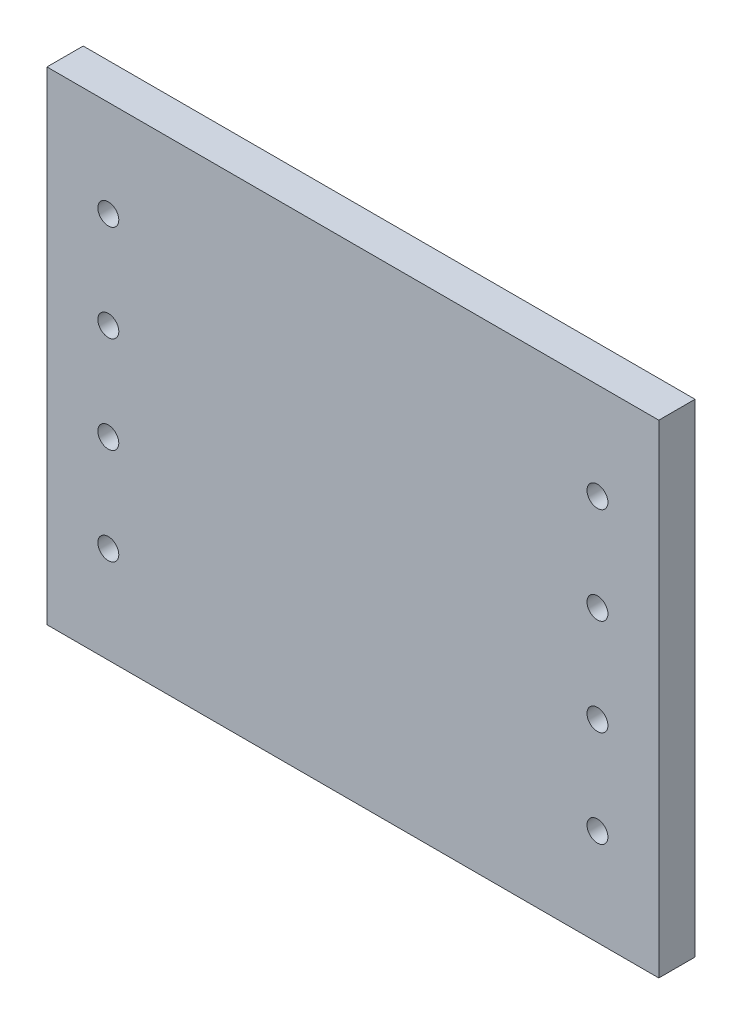
SolidWorks part; units mm, degrees
ref_plane "Front" through (0, 0, 0) normal (0, 0, 1) x (1, 0, 0)
ref_plane "Top" through (0, 0, 0) normal (0, 1, 0) x (1, 0, 0)
ref_plane "Right" through (0, 0, 0) normal (1, 0, 0) x (0, 0, -1)
other "Configuration Table"
sketch "Sketch1" plane through (0, 0, 0) normal (0, 0, 1) x (1, 0, 0)
  line L1 (23.481, 212.5625) -> (345.172, 212.5625)
  line L2 (345.172, 441.1625) -> (345.172, 237.9625) construction
  line L3 (23.481, 466.5625) -> (345.172, 466.5625)
  line L4 (345.172, 212.5625) -> (345.172, 466.5625)
  line L5 (345.172, 441.1625) -> (345.172, 237.9625) construction
  line L6 (23.481, 466.5625) -> (23.481, 212.5625)
  dimension "D2" = 254
extrude "Base-Extrude" add sketch "Sketch1" along normal blind 19.05
sketch "Sketch2" plane through (0, 0, 0) normal (0, 0, -1) x (-1, 0, 0)
  line L1 (-345.172, 466.5625) -> (-23.481, 466.5625) construction
  line L2 (-345.172, 466.5625) -> (-23.481, 466.5625) construction
  line L3 (-273.2265, 392.2739) -> (-273.2265, 245.7761)
  line L4 (-23.481, 212.5625) -> (-345.172, 212.5625) construction
  line L5 (-105.1421, 403.0625) -> (-263.511, 403.0625)
  line L6 (-105.1421, 403.0625) -> (-95.4265, 392.2739)
  line L7 (-263.511, 403.0625) -> (-273.2265, 392.2739)
  line L8 (-273.2265, 245.7761) -> (-95.4265, 245.7761)
  line L9 (-95.4265, 392.2739) -> (-95.4265, 245.7761)
  line L10 (-23.481, 212.5625) -> (-345.172, 212.5625) construction
  line L11 (-184.3265, 466.5625) -> (-184.3265, 212.5625) construction
  dimension "D1" = 177.8
extrude "Boss-Extrude1" add sketch "Sketch2" along normal blind 15.875
sketch "Sketch3" plane through (0, 0, -15.875) normal (0, 0, -1) x (-1, 0, 0)
  line L24 (-254.1765, 264.8261) -> (-114.4765, 264.8261)
  line L25 (-114.4765, 264.8261) -> (-114.4765, 384.0125)
  line L26 (-114.4765, 384.0125) -> (-254.1765, 384.0125)
  line L27 (-254.1765, 384.0125) -> (-254.1765, 264.8261)
  line L28 (-254.1765, 264.8261) -> (-114.4765, 264.8261)
  line L29 (-114.4765, 264.8261) -> (-114.4765, 384.0125)
  line L30 (-114.4765, 384.0125) -> (-254.1765, 384.0125)
  line L31 (-254.1765, 384.0125) -> (-254.1765, 264.8261)
  dimension "D2" = 19.05
extrude "Cut-Extrude1" cut sketch "Sketch3" against normal up to surface (15.875 mm away) up to face at (184.3265, 339.5625, 0)
fillet "Fillet3" radius 2.54 6 edges at (95.4265, 319.025, 0) (100.2843, 397.6682, 0) (184.3265, 403.0625, 0) (268.3688, 397.6682, 0) (273.2265, 319.025, 0) (184.3265, 245.7761, 0)
fillet "Fillet5" radius 6.35 4 edges at (254.1765, 264.8261, -7.9375) (114.4765, 264.8261, -7.9375) (114.4765, 384.0125, -7.9375) (254.1765, 384.0125, -7.9375)
fillet "Fillet6" radius 2.54 8 edges at (254.1765, 324.4193, 0) (184.3265, 384.0125, 0) (184.3265, 264.8261, 0) (114.4765, 324.4193, 0) (116.3364, 266.686, 0) (116.3364, 382.1526, 0) (252.3167, 266.686, 0) (252.3167, 382.1526, 0)
hole_wizard "CBORE for M10 SHCS1" positions "Sketch7" profile "Sketch6" counterbore size "M10" standard "Ansi Metric" end condition through all
sketch "Sketch7" plane through (0, 0, 0) normal (0, 0, -1) x (-1, 0, 0)
  line L0 (-345.172, 212.5625) -> (-345.172, 466.5625) construction
  line L1 (-345.172, 466.5625) -> (-23.481, 466.5625) construction
  point P0 (-312.914, 415.7625)
  dimension "D1" = 32.258
  dimension "D2" = 50.8
sketch "Sketch6" plane through (312.914, 415.7625, 0) normal (1, 0, 0) x (0, 1, 0)
  line L0 (0, 0) -> (0, 19.05)
  line L1 (0, 19.05) -> (5.5, 19.05)
  line L3 (5.5, 19.05) -> (5.5, 10)
  line L4 (5.5, 10) -> (9, 10)
  line L5 (9, 10) -> (9, 0)
  line L7 (9, 0) -> (0, 0)
  line L11 (0, -6.35) -> (0, 107.95) construction
  dimension "Thru Hole Dia." = 11
  dimension "Thru Hole Depth" = 19.05
  dimension "C'Bore Dia." = 18
  dimension "C'Bore Depth" = 10
pattern_linear "LPattern1" count 4 spacing 50.8 along (0, -1, 0) of "CBORE for M10 SHCS1"
hole_wizard "CBORE for M10 SHCS2" positions "Sketch9" profile "Sketch8" counterbore size "M10" standard "Ansi Metric" end condition through all
sketch "Sketch9" plane through (0, 0, 0) normal (0, 0, -1) x (-1, 0, 0)
  line L0 (-23.481, 466.5625) -> (-23.481, 212.5625) construction
  line L1 (-345.172, 466.5625) -> (-23.481, 466.5625) construction
  point P0 (-55.739, 415.7625)
  dimension "D1" = 32.258
  dimension "D2" = 50.8
sketch "Sketch8" plane through (55.739, 415.7625, 0) normal (1, 0, 0) x (0, 1, 0)
  line L0 (0, 0) -> (0, 19.05)
  line L1 (0, 19.05) -> (5.5, 19.05)
  line L3 (5.5, 19.05) -> (5.5, 10)
  line L4 (5.5, 10) -> (9, 10)
  line L5 (9, 10) -> (9, 0)
  line L7 (9, 0) -> (0, 0)
  line L11 (0, -6.35) -> (0, 107.95) construction
  dimension "Thru Hole Dia." = 11
  dimension "Thru Hole Depth" = 19.05
  dimension "C'Bore Dia." = 18
  dimension "C'Bore Depth" = 10
pattern_linear "LPattern2" count 4 spacing 50.8 along (0, -1, 0) of "CBORE for M10 SHCS2"
